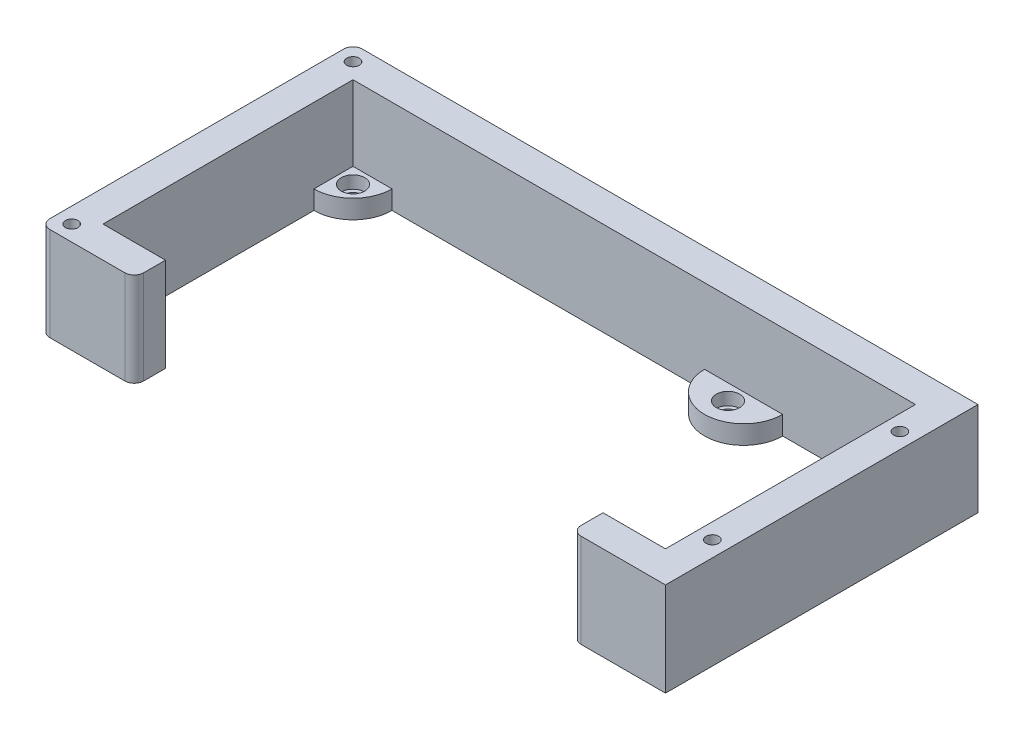
SolidWorks part; units mm, degrees
ref_plane "Front Plane" through (0, 0, 0) normal (0, 0, 1) x (1, 0, 0)
ref_plane "Top Plane" through (0, 0, 0) normal (0, 1, 0) x (1, 0, 0)
ref_plane "Right Plane" through (0, 0, 0) normal (1, 0, 0) x (0, 0, -1)
sketch "Sketch1" plane through (0, 0, 0) normal (0, 1, 0) x (1, 0, 0)
  line L0 (0, 0) -> (-102297.8204, 0) construction
  line L1 (0, 0) -> (0, -102297.8204) construction
  line L2 (-90, 40) -> (-90, -40)
  line L3 (-100, 50) -> (100, 50)
  line L4 (-100, 50) -> (-100, -50)
  line L5 (-100, -50) -> (100, -50)
  line L6 (100, 50) -> (100, -50)
  line L7 (-100, 50) -> (100, -50) construction
  line L8 (-100, -50) -> (100, 50) construction
  line L9 (-90, -40) -> (90, -40)
  line L10 (90, 40) -> (90, -40)
  line L11 (-90, 40) -> (90, 40)
  point P5 (0, 0)
  dimension "D1" = 100
  dimension "D2" = 200
  dimension "D3" = 10
extrude "Boss-Extrude1" add sketch "Sketch1" along normal blind 30
sketch "Sketch2" plane through (0, 0, 0) normal (0, 1, 0) x (1, 0, 0)
  line L0 (0, 0) -> (-50000, 0) construction
  line L1 (0, 0) -> (0, -50000) construction
  line L2 (70, -20) -> (70, 20) construction
  line L3 (70, 20) -> (-70, 20) construction
  line L4 (-70, 20) -> (-70, -20) construction
  line L5 (-70, -20) -> (70, -20) construction
  line L6 (100, -50) -> (100, 50)
  line L7 (100, 50) -> (-100, 50)
  line L8 (-100, 50) -> (-100, -50)
  line L9 (-100, -50) -> (100, -50)
  line L10 (100, -50) -> (100, 50) construction
  line L11 (100, 50) -> (-100, 50) construction
  line L12 (-100, 50) -> (-100, -50) construction
  line L13 (-100, -50) -> (100, -50) construction
  line L14 (-70, 20) -> (-100, 50) construction
  line L15 (-90, 40) -> (-77.5, 40)
  line L16 (-90, 40) -> (-90, 27.5)
  line L21 (-90, -40) -> (-90, -27.5)
  line L22 (-90, -40) -> (-77.5, -40)
  line L23 (35, 35) -> (35, -49965) construction
  line L24 (35, 35) -> (-49965, 35) construction
  line L25 (90, 40) -> (-90, 40) construction
  line L26 (22.5, 40) -> (47.5, 40)
  circle A0 centre (-85, 35) radius 2.5
  arc A1 (-90, 27.5) -> (-77.5, 40) centre (-90, 40) ccw
  arc A6 (-90, -27.5) -> (-77.5, -40) centre (-90, -40) cw
  circle A7 centre (-85, -35) radius 2.5
  circle A8 centre (35, 35) radius 2.5
  arc A9 (22.5, 40) -> (47.5, 40) centre (35, 40) ccw
  dimension "D3" = 5
  dimension "D4" = 25
  dimension "D5" = 5
  dimension "D6" = 120
  dimension "D7" = 25
  dimension "D1" = 0
  dimension "D2" = 30
extrude "Boss-Extrude2" add sketch "Sketch2" along normal blind 6
sketch "Sketch3" plane through (0, 6, 0) normal (0, 1, 0) x (1, 0, 0)
  line L0 (0, 0) -> (-50000, 0) construction
  line L1 (0, 0) -> (0, -50000) construction
  circle A0 centre (-85, 35) radius 3.75
  circle A3 centre (-85, -35) radius 3.75
  circle A4 centre (35, 35) radius 3.75
  dimension "D1" = 7.5
  dimension "D2" = 7.5
extrude "Cut-Extrude1" cut sketch "Sketch3" against normal blind 4
sketch "Sketch4" plane through (0, 30, 0) normal (0, 1, 0) x (1, 0, 0)
  line L0 (0, 0) -> (-50000, 0) construction
  line L1 (0, 0) -> (0, -50000) construction
  line L2 (-90, 40) -> (-100, 50) construction
  line L3 (95, 50) -> (95, -49950) construction
  line L10 (100, -50) -> (100, 50) construction
  line L11 (100, 50) -> (-100, 50) construction
  circle A0 centre (-95, 45) radius 2
  circle A3 centre (-95, -45) radius 2
  circle A12 centre (95, 30) radius 2
  circle A13 centre (95, -30) radius 2
  dimension "D1" = 4
  dimension "D3" = 4
  dimension "D4" = 20
  dimension "D2" = 5
extrude "Cut-Extrude2" cut sketch "Sketch4" against normal blind 15
sketch "Sketch5" plane through (0, 30, 0) normal (0, 1, 0) x (1, 0, 0)
  line L0 (0, 0) -> (-50000, 0) construction
  line L1 (0, 0) -> (0, -50000) construction
  line L2 (-95, -45) -> (49905, -45) construction
  line L3 (-100, -50) -> (100, -50) construction
  line L4 (-70, -40) -> (70, -40)
  line L5 (-70, -40) -> (-70, -50)
  line L6 (-70, -50) -> (70, -50)
  line L7 (70, -40) -> (70, -50)
  line L8 (-70, -40) -> (70, -50) construction
  line L9 (-70, -50) -> (70, -40) construction
  point P8 (0, -45)
  dimension "D1" = 140
extrude "Cut-Extrude4" cut sketch "Sketch5" against normal through all
fillet "Fillet1" radius 3 4 edges at (70, 15, 50) (-70, 15, 50) (-100, 15, 50) (-100, 15, -50)
